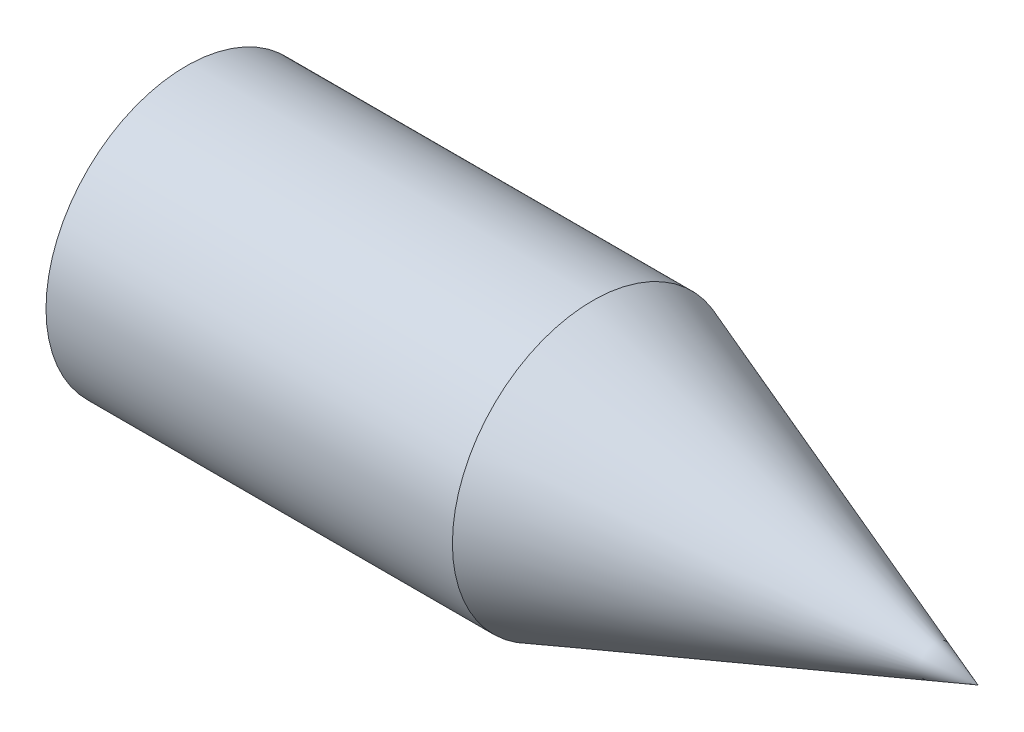
SolidWorks part; units mm, degrees
ref_plane "Ebene vorne" through (0, 0, 0) normal (0, 0, 1) x (1, 0, 0)
ref_plane "Ebene oben" through (0, 0, 0) normal (0, 1, 0) x (1, 0, 0)
ref_plane "Ebene rechts" through (0, 0, 0) normal (1, 0, 0) x (0, 0, -1)
sketch "Skizze1" plane through (0, 0, 0) normal (0, 0, 1) x (1, 0, 0)
  line L0 (0, 0) -> (25.0252, 0) construction
  line L1 (0, 5) -> (0, 6.2)
  line L2 (0, 6.2) -> (17.9656, 6.2)
  line L3 (17.9656, 6.2) -> (35, 0)
  line L4 (35, 0) -> (16, 0)
  line L5 (16, 0) -> (16, 5)
  line L6 (16, 5) -> (0, 5)
  point P5 (0, 0)
  point P10 (0, 0)
  point P11 (0, 0)
  dimension "D1" = 10
  dimension "D2" = 12.4
  dimension "D3" = 20
  dimension "D4" = 35
  dimension "D5" = 16
revolve "Rotation1" add sketch "Skizze1" angle 360 about L0
